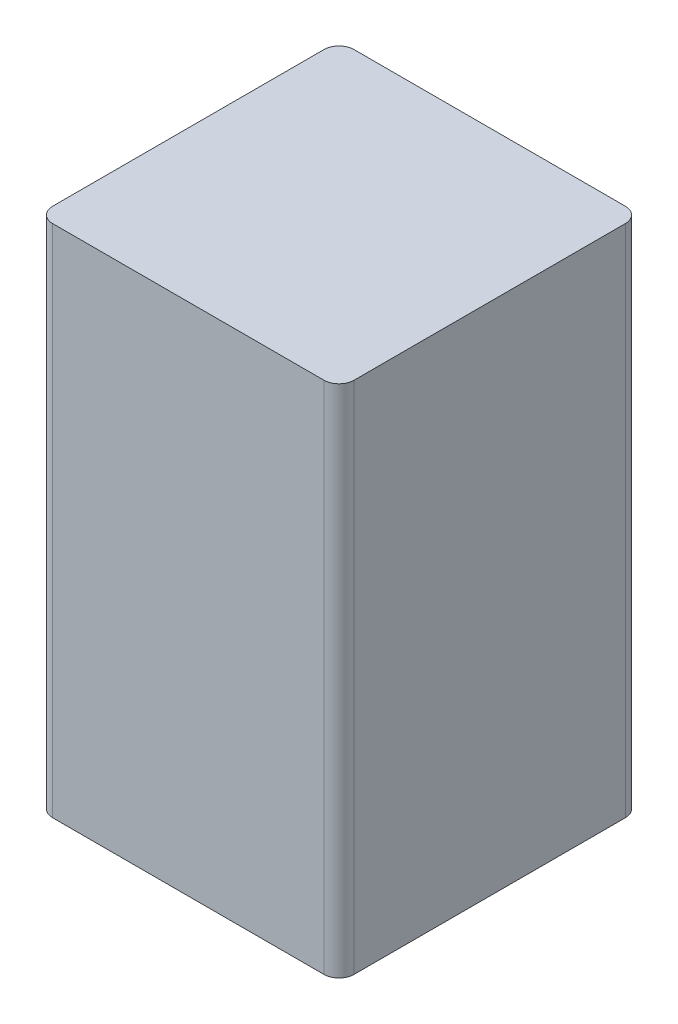
SolidWorks part; units mm, degrees
ref_plane "前视基准面" through (0, 0, 0) normal (0, 0, 1) x (1, 0, 0)
ref_plane "上视基准面" through (0, 0, 0) normal (0, 1, 0) x (1, 0, 0)
ref_plane "右视基准面" through (0, 0, 0) normal (1, 0, 0) x (0, 0, -1)
other "Configuration Table"
sketch "草图1" plane through (0, 0, 0) normal (0, 0, 1) x (1, 0, 0)
  line L0 (0, 0) -> (40, 0)
  line L1 (40, 0) -> (40, 68.3)
  line L2 (40, 68.3) -> (0, 68.3)
  line L3 (0, 68.3) -> (0, 0)
  dimension "width" = 40
  dimension "height" = 68.3
extrude "BlockExtrude" add sketch "草图1" along normal blind 40
fillet "Fillet" radius 2 4 edges at (0, 34.15, 0) (40, 34.15, 0) (0, 34.15, 40) (40, 34.15, 40)
